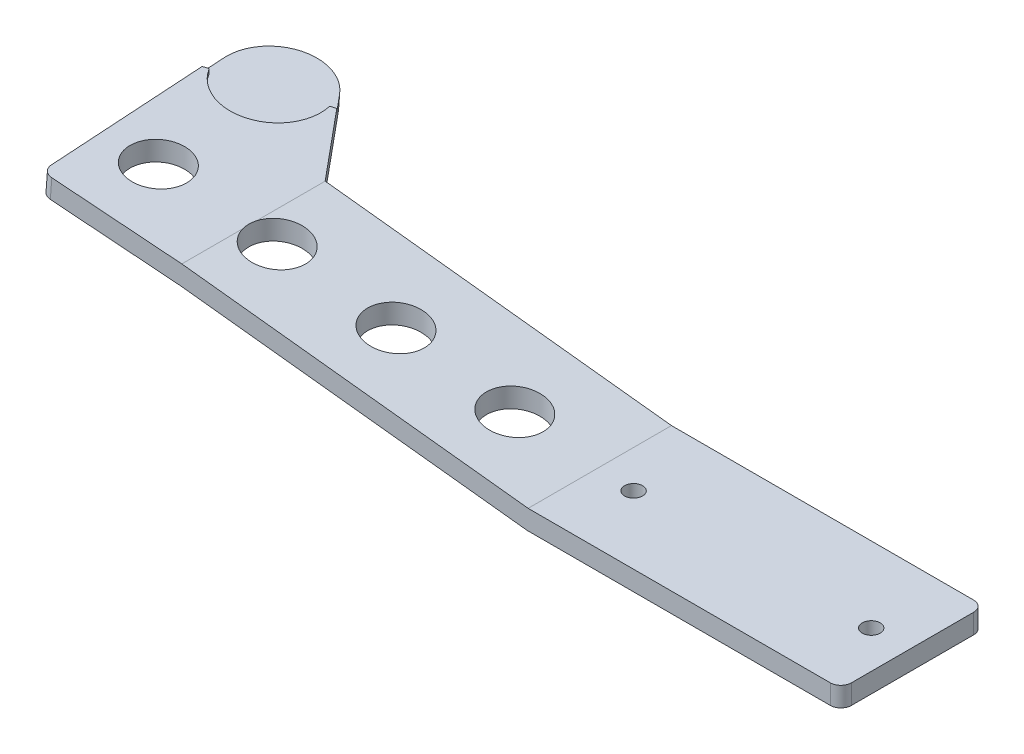
SolidWorks part; units mm, degrees
ref_plane "Front Plane" through (0, 0, 0) normal (0, 0, 1) x (1, 0, 0)
ref_plane "Top Plane" through (0, 0, 0) normal (0, 1, 0) x (1, 0, 0)
ref_plane "Right Plane" through (0, 0, 0) normal (1, 0, 0) x (0, 0, -1)
sketch "Sketch1" plane through (0, 0, 0) normal (0, 0, 1) x (1, 0, 0)
  line L0 (0, 0) -> (-52.832, 0)
  line L1 (0, 0) -> (0, 3.302)
  line L2 (0, 3.302) -> (-52.6489, 3.302)
  line L3 (-82.042, 3.2494) -> (-81.6769, 6.5311) construction
  line L4 (-52.6489, 3.302) -> (-110.9473, 9.7873)
  line L6 (-111.252, 6.4988) -> (-52.832, 0)
  line L7 (-110.9473, 9.7873) -> (-136.4079, 11.675)
  line L8 (-136.4079, 11.675) -> (-136.652, 8.382)
  line L9 (-136.652, 8.382) -> (-111.252, 6.4988)
  dimension "D1" = 52.832
  dimension "D2" = 3.302
  dimension "D3" = 58.42
  dimension "D4" = 177.893
  dimension "D5" = 25.4
  dimension "D6" = 8.382
extrude "Boss-Extrude1" add sketch "Sketch1" along normal blind 24.13
sketch "Sketch2" plane through (0, 3.302, 0) normal (0, 1, 0) x (1, 0, 0)
  line L0 (0, -12.7) -> (-6.3245, -12.7) construction
  line L1 (0, -24.13) -> (0, 0) construction
  line L2 (-6.3245, -12.7) -> (-26.3245, -12.7) construction
  line L3 (-46.3245, -12.7) -> (-52.6489, -12.7) construction
  line L4 (-52.6489, -24.13) -> (-52.6489, 0) construction
  line L5 (-46.3245, -12.7) -> (-66.3245, -12.7) construction
  line L6 (-66.3245, -12.7) -> (-86.3245, -12.7) construction
  line L7 (-86.3245, -12.7) -> (-106.3245, -12.7) construction
  line L8 (-106.3245, -12.7) -> (-126.3245, -12.7) construction
  line L9 (-26.3245, -12.7) -> (-46.3245, -12.7) construction
  line L10 (-46.3245, -12.7) -> (-46.3245, -20.637) construction
  line L11 (-46.3245, -20.637) -> (-66.3245, -20.637) construction
  line L12 (-66.3245, -20.637) -> (-66.3245, -12.7) construction
  circle A0 centre (-6.3245, -12.7) radius 1.5113
  circle A1 centre (-46.3245, -12.7) radius 1.5113
  circle A2 centre (-66.3245, -12.7) radius 4.7625
  circle A3 centre (-86.3245, -12.7) radius 4.7625
  circle A4 centre (-106.3245, -12.7) radius 4.7625
  circle A5 centre (-126.3245, -12.7) radius 4.7625
  dimension "D1" = 3.0226
  dimension "D4" = 9.525
  dimension "D2" = 20
  dimension "D3" = 11.43
extrude "Cut-Extrude1" cut sketch "Sketch2" against normal through all both and the other way through all
sketch "Sketch3" plane through (0.1151, 1.5528, 0) normal (0.0739, 0.9973, 0) x (0.9973, -0.0739, 0)
  line L0 (-136.8977, 0) -> (-136.8977, 8.89)
  line L1 (-111.3673, 0) -> (-122.8307, 13.9331)
  line L2 (-111.3673, 0) -> (-136.8977, 0)
  arc A0 (-122.8307, 13.9331) -> (-136.8977, 8.89) centre (-128.9602, 8.89) ccw
  dimension "D1" = 15.875
  dimension "D2" = 8.89
extrude "Boss-Extrude2" add sketch "Sketch3" against normal up to surface (3.302 mm away) up to face at (-131.087, 7.9694, 12.7)
sketch "Sketch4" plane through (0.1151, 1.5528, 0) normal (0.0739, 0.9973, 0) x (0.9973, -0.0739, 0)
  line L0 (-136.8977, 8.89) -> (-134.9927, -24.13)
  line L1 (-111.3673, -24.13) -> (-136.8977, -24.13) construction
  line L2 (-134.9927, -24.13) -> (-136.8977, -24.13)
  line L3 (-136.8977, -24.13) -> (-138.8027, -24.13)
  line L4 (-138.8027, -24.13) -> (-138.8027, 8.89)
  line L5 (-138.8027, 8.89) -> (-136.8977, 8.89)
  dimension "D1" = 1.905
extrude "Cut-Extrude2" cut sketch "Sketch4" against normal through all and the other way through all
fillet "Fillet1" radius 1.778 3 edges at (0, 1.651, 24.13) (0, 1.651, 0) (-134.6301, 9.8876, 24.13)
sketch "Sketch5" plane through (0.1151, 1.5528, 0) normal (0.0739, 0.9973, 0) x (0.9973, -0.0739, 0)
  line L0 (-135.7869, 4.8403) -> (-136.6446, 4.503)
  line L1 (-136.8977, 8.89) -> (-135.0894, -22.4544) construction
  line L2 (-120.3461, 10.9133) -> (-121.2038, 10.5759)
  line L3 (-111.3673, 0) -> (-122.8307, 13.9331) construction
  line L4 (-122.8307, 13.9331) -> (-120.3461, 10.9133)
  line L5 (-136.883, 8.4062) -> (-136.6446, 4.503)
  line L6 (-121.2038, 10.5759) -> (-135.7869, 4.8403) construction
  line L7 (-128.9602, 8.89) -> (-128.4954, 7.7081) construction
  line L8 (-136.883, 8.4062) -> (-122.8307, 13.9331) construction
  line L9 (-128.9602, 8.89) -> (-129.8568, 11.1696) construction
  arc A0 (-135.7869, 4.8403) -> (-121.2038, 10.5759) centre (-128.9602, 8.89) ccw
  arc A1 (-122.8307, 13.9331) -> (-136.8977, 8.89) centre (-128.9602, 8.89) ccw construction
  arc A2 (-122.8307, 13.9331) -> (-136.883, 8.4062) centre (-128.9602, 8.89) ccw
  dimension "D1" = 1.27
extrude "Cut-Extrude3" cut sketch "Sketch5" against normal blind 0.889
